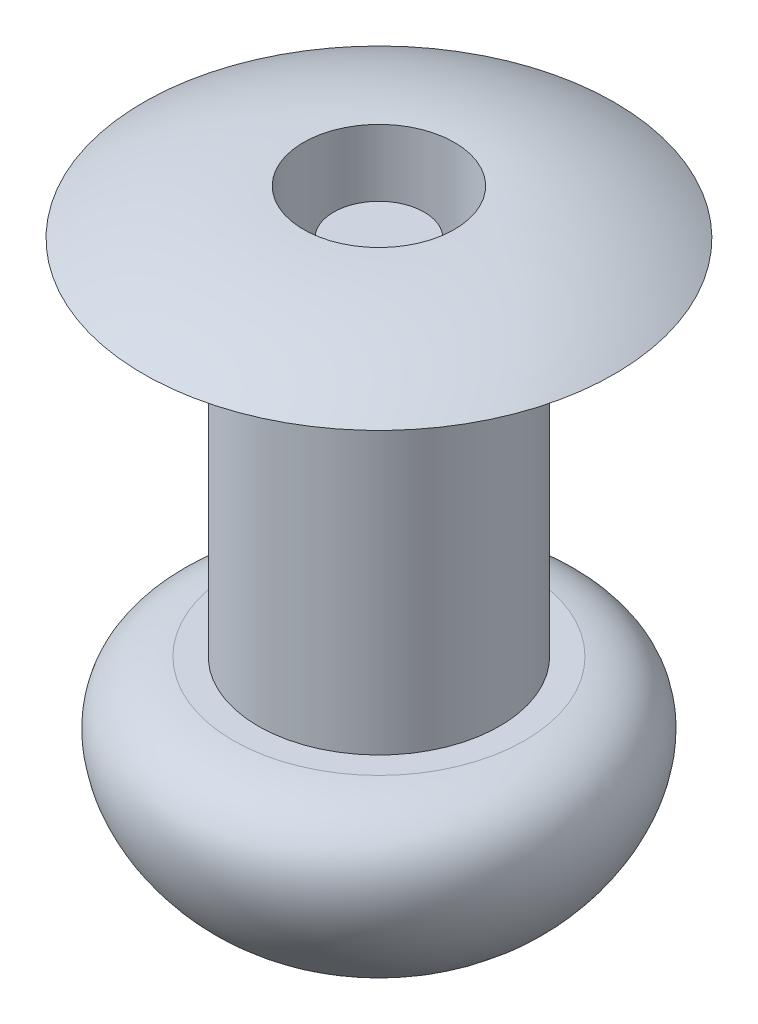
SolidWorks part; units mm, degrees
material "AISI 316 Stal nierdzewna odprężona (SS)"
ref_plane "Płaszczyzna przednia" through (0, 0, 0) normal (0, 0, 1) x (1, 0, 0)
ref_plane "Płaszczyzna górna" through (0, 0, 0) normal (0, 1, 0) x (1, 0, 0)
ref_plane "Płaszczyzna prawa" through (0, 0, 0) normal (1, 0, 0) x (0, 0, -1)
sketch "Szkic1" plane through (0, 0, 0) normal (1, 0, 0) x (0, 0, -1)
  line L0 (0, 0) -> (0, -6)
  line L1 (0, 0) -> (-0.75, 0)
  line L2 (-0.75, 0) -> (-0.75, -6)
  line L3 (-0.75, -6) -> (-1.25, -6)
  line L4 (-1.25, -6) -> (-1.25, 0.75)
  line L5 (-3.9, 0) -> (-2, 0)
  line L6 (-2, 0) -> (-2, -6)
  line L7 (-2, -6) -> (-2.4139, -6)
  line L8 (0, 0) -> (0, 0.4842) construction
  line L10 (0, -6) -> (0, -7.5)
  arc A0 (-1.25, 0.75) -> (-3.9, 0) centre (-1.25, -4.3067) ccw
  ellipse E0 centre (0, -6.75) end of major axis (-1.75, -6.75) minor radius 0.75 (-0.956, -7.3782) -> (0, -7.5) ccw
  spline S0 degree 3 poles (-2.4139, -6) (-3.8586, -6.1633) (-3.5584, -8.323) (-0.9713, -9.8719) (-0.3411, -7.792) (-0.956, -7.3782) knots 0 0 0 0 0.454219 0.705201 1 1 1 1
  point P14 (0, 0)
  point P15 (0, -5.7354)
  point P27 (0, -8.5654)
  dimension "D1" = 7.8
  dimension "D2" = 2.5
  dimension "D3" = 4
  dimension "D4" = 0.75
  dimension "D5" = 1.5
  dimension "D6" = 1.5
  dimension "D7" = 3.5
  dimension "D8" = 3.1855
  dimension "D9" = 2.5026
  dimension "D10" = 1.9
  dimension "D11" = 1.3782
  dimension "D12" = 0.5792
  dimension "D13" = 4.8278
  dimension "D14" = 3.3858
  dimension "D15" = 2.8395
  dimension "D16" = 1.25
  dimension "D17" = 0.6409
  dimension "D18" = 0.956
  dimension "D19" = 6
revolve "Obrót1" add sketch "Szkic1" angle 360 about L8
